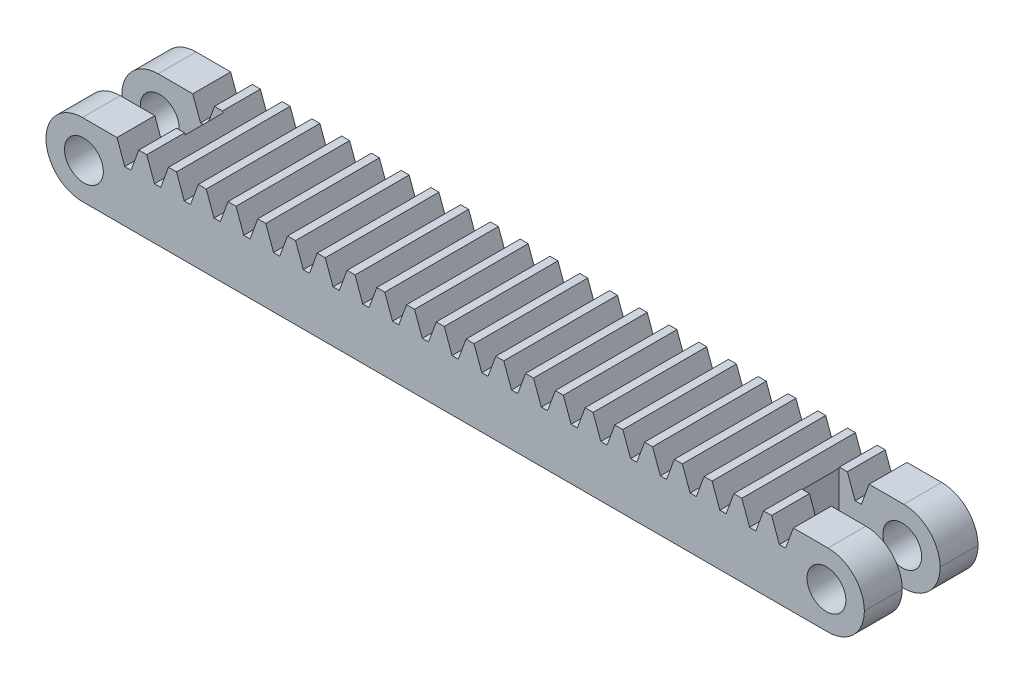
SolidWorks part; units mm, degrees
ref_plane "Front Plane" through (0, 0, 0) normal (0, 0, 1) x (1, 0, 0)
ref_plane "Top Plane" through (0, 0, 0) normal (0, 1, 0) x (1, 0, 0)
ref_plane "Right Plane" through (0, 0, 0) normal (1, 0, 0) x (0, 0, -1)
sketch "Sketch6" plane through (0, 0, 0) normal (0, 0, 1) x (1, 0, 0)
  line L1 (0, 0) -> (62.23, 0)
  line L2 (0, 0) -> (0, 2.032)
  line L3 (0, 2.032) -> (62.23, 2.032)
  line L4 (62.23, 0) -> (62.23, 2.032)
  dimension "D1" = 62.23
  dimension "D2" = 2.032
extrude "Boss-Extrude2" add sketch "Sketch6" along normal mid plane 6.35
sketch "Sketch7" plane through (0, 0, 0) normal (0, 0, 1) x (1, 0, 0)
  line L1 (0, 2.032) -> (0, 0) construction
  line L2 (0, 2.032) -> (1.969, 2.032)
  line L3 (62.23, 2.032) -> (0, 2.032) construction
  line L4 (0, 2.032) -> (1.969, 2.032)
  line L6 (1.319, 3.8179) -> (0.65, 3.8179)
  line L7 (0, 2.032) -> (0.65, 3.8179)
  line L8 (1.319, 3.8179) -> (1.969, 2.032)
  line L9 (1.969, 2.032) -> (1.969, 2.4475) construction
  point P4 (0, 3.556)
  point P6 (0, 1.016)
  point P16 (0.9845, 3.8179)
  dimension "D1" = 2.54
  dimension "D2" = 1.969
  dimension "D4" = 0.669
extrude "Boss-Extrude3" add sketch "Sketch7" along normal mid plane 6.35 contours L8 L6 L7 L2
pattern_linear "LPattern2" count 24 spacing 2.4935 along (1, 0, 0) of "Boss-Extrude3"
sketch "Sketch9" plane through (0, 0, 0) normal (0, 0, 1) x (1, 0, 0)
  line L2 (59.3199, 2.032) -> (62.23, 2.032)
  line L3 (59.3199, 2.032) -> (59.3199, 0)
  line L4 (59.3199, 0) -> (62.23, 0)
  line L5 (62.23, 2.032) -> (62.23, 0)
extrude "Cut-Extrude1" cut sketch "Sketch9" against normal mid plane 6.35
sketch "Sketch10" plane through (0, 0, 0) normal (0, -1, 0) x (1, 0, 0)
  line L4 (0, -3.175) -> (59.3199, -3.175)
  line L5 (59.3199, -3.175) -> (59.3199, 3.175)
  line L6 (59.3199, 3.175) -> (0, 3.175)
  line L7 (0, 3.175) -> (0, -3.175)
  line L8 (0, -3.175) -> (59.3199, -3.175)
  line L9 (59.3199, -3.175) -> (59.3199, 3.175)
  line L10 (59.3199, 3.175) -> (0, 3.175)
  line L11 (0, 3.175) -> (0, -3.175)
  dimension "D1" = 0
extrude "Boss-Extrude4" add sketch "Sketch10" along normal blind 0.508
sketch "Sketch11" plane through (0, 0, 3.175) normal (0, 0, 1) x (1, 0, 0)
  line L0 (59.3199, -0.508) -> (0, -0.508) construction
  line L1 (63.95, -0.508) -> (-4.63, -0.508)
  line L2 (63.95, -0.508) -> (63.95, 2.032)
  line L3 (63.95, 2.032) -> (-4.63, 2.032)
  line L4 (-4.63, -0.508) -> (-4.63, 2.032)
  point P7 (29.66, -0.508)
  point P8 (29.66, -0.508)
  dimension "D1" = 68.58
extrude "Boss-Extrude5" add sketch "Sketch11" against normal up to surface (6.35 mm away)
sketch "Sketch12" plane through (0, -0.508, 0) normal (0, -1, 0) x (1, 0, 0)
  line L1 (-4.63, 3.175) -> (1.72, 3.175)
  line L2 (-4.63, 3.175) -> (-4.63, -3.175)
  line L3 (-4.63, -3.175) -> (1.72, -3.175)
  line L4 (1.72, 3.175) -> (1.72, -3.175)
  line L6 (-4.63, -3.175) -> (63.95, -3.175) construction
  dimension "D1" = 6.35
extrude "Boss-Extrude6" add sketch "Sketch12" along normal blind 1.778
ref_plane "Plane1" through (29.66, 0, 0) normal (-1, 0, 0) x (0, 0, 1)
sketch "Sketch13" plane through (0, 0, 3.175) normal (0, 0, 1) x (1, 0, 0)
  line L0 (29.66, 55) -> (29.66, -55) construction
  line L1 (9.7118, 2.032) -> (9.7118, -0.508) construction
  line L2 (9.9741, 2.032) -> (9.4496, 2.032) construction
  line L3 (63.95, -0.508) -> (1.72, -0.508) construction
  circle A0 centre (-1.455, 0.762) radius 1.627
  point P10 (9.7118, 0.762)
  dimension "D2" = 3.254
  dimension "D1" = 31.115
sketch "Sketch14" plane through (0, 0, 3.175) normal (0, 0, 1) x (1, 0, 0)
  line L1 (0, 2.032) -> (0.65, 3.8179) construction
  line L2 (-4.63, 2.925) -> (-4.63, 2.032)
  line L3 (-4.63, 2.032) -> (-4.63, -2.286) construction
  line L4 (0, 2.032) -> (-4.63, 2.032) construction
  line L5 (0, 2.032) -> (-4.63, 2.032)
  line L6 (0, 2.032) -> (0.325, 2.925)
  line L7 (0.65, 3.8179) -> (-4.63, 3.8179)
  line L8 (-4.63, 3.8179) -> (-4.63, 2.925)
  line L9 (0.65, 3.8179) -> (0.325, 2.925)
  line L11 (32.835, -2.286) -> (32.835, -0.508)
  line L12 (63.95, -0.508) -> (1.72, -0.508) construction
  line L14 (1.72, -0.508) -> (1.72, -2.286)
  line L17 (1.72, -0.508) -> (32.835, -0.508)
  line L18 (1.72, -2.286) -> (32.835, -2.286)
  point P16 (32.835, -0.508)
extrude "Boss-Extrude7" add sketch "Sketch14" against normal up to surface (6.35 mm away)
extrude "Cut-Extrude2" cut sketch "Sketch13" against normal up to next
fillet "Fillet1" radius 3.048 2 edges at (-4.63, 3.8179, 0) (-4.63, -2.286, 0)
mirror "Mirror4" about plane through (29.66, 0, 0) normal (-1, 0, 0) of "Boss-Extrude6", "Fillet1", "Boss-Extrude7", "Cut-Extrude2"
sketch "Sketch16" plane through (0, 3.8179, 0) normal (0, 1, 0) x (1, 0, 0)
  line L0 (1.319, -3.175) -> (1.319, 3.175) construction
  line L1 (1.319, 0) -> (-4.63, 0)
  line L2 (1.319, 0) -> (1.319, -3.175)
  line L3 (1.319, -3.175) -> (-4.63, -3.175)
  line L4 (-4.63, 0) -> (-4.63, -3.175)
  line L5 (58.0009, -3.175) -> (58.0009, 3.175) construction
  line L6 (63.95, -3.175) -> (58.0009, -3.175)
  line L7 (63.95, -3.175) -> (63.95, 0)
  line L8 (63.95, 0) -> (58.0009, 0)
  line L9 (58.0009, -3.175) -> (58.0009, 0)
extrude "Cut-Extrude3" cut sketch "Sketch16" against normal up to next
ref_plane "Plane2" through (0, 0, 1.5875) normal (0, 0, 1) x (1, 0, 0)
sketch "Sketch18" plane through (0, 0, 1.5875) normal (0, 0, 1) x (1, 0, 0)
  line L1 (-5.157, 13.6315) -> (69.1289, 13.6315)
  line L2 (-5.157, 13.6315) -> (-5.157, -9.7009)
  line L3 (-5.157, -9.7009) -> (69.1289, -9.7009)
  line L4 (69.1289, 13.6315) -> (69.1289, -9.7009)
extrude "Cut-Extrude4" cut sketch "Sketch18" along normal up to next
mirror "Mirror11" about plane through (0, 0, 1.5875) normal (0, 0, 1) of bodies 117
sketch "Sketch19" plane through (58.0009, 0, 0) normal (1, 0, 0) x (0, 0, -1)
  line L4 (0, 3.8179) -> (-3.175, 3.8179)
  line L5 (-3.175, 3.8179) -> (-3.175, -2.286)
  line L6 (-3.175, -2.286) -> (0, -2.286)
  line L7 (0, -2.286) -> (0, 3.8179)
  line L8 (0, 3.8179) -> (-3.175, 3.8179)
  line L9 (-3.175, 3.8179) -> (-3.175, -2.286)
  line L10 (-3.175, -2.286) -> (0, -2.286)
  line L11 (0, -2.286) -> (0, 3.8179)
  dimension "D1" = 0
extrude "Cut-Extrude5" cut sketch "Sketch19" against normal blind 2.54
sketch "Sketch20" plane through (1.319, 0, 0) normal (-1, 0, 0) x (0, 0, 1)
  line L4 (0, -2.286) -> (3.175, -2.286)
  line L5 (3.175, -2.286) -> (3.175, 3.8179)
  line L6 (3.175, 3.8179) -> (0, 3.8179)
  line L7 (0, 3.8179) -> (0, -2.286)
  line L8 (0, -2.286) -> (3.175, -2.286)
  line L9 (3.175, -2.286) -> (3.175, 3.8179)
  line L10 (3.175, 3.8179) -> (0, 3.8179)
  line L11 (0, 3.8179) -> (0, -2.286)
  dimension "D1" = 0
extrude "Cut-Extrude6" cut sketch "Sketch20" against normal blind 2.54
equation "\"L\"= 2.45in"
equation "\"DP\"= 32"
equation "\"phi\"= 20deg"
equation "\"Nr\"= 24"
equation "\"rackThk\"= 0.250in"
equation "\"PIc\"= 3.14159265358979"
equation "\"p\"= \"PIc\" / \"DP\""
equation "\"a\"= 1 / \"DP\""
equation "\"b\"= 1.25 / \"DP\""
equation "\"h\"= \"a\" + \"b\""
equation "\"t\"= \"p\" / 2"
equation "\"tTop\"= \"t\" - 2 * \"a\" * TAN ( \"phi\" )"
equation "\"tBot\"= \"t\" + 2 * \"b\" * TAN ( \"phi\" )"
equation "\"M\"= ( \"L\" - \"Nr\" * \"p\" ) / 2"
equation "\"backing\"= 0.080in"
